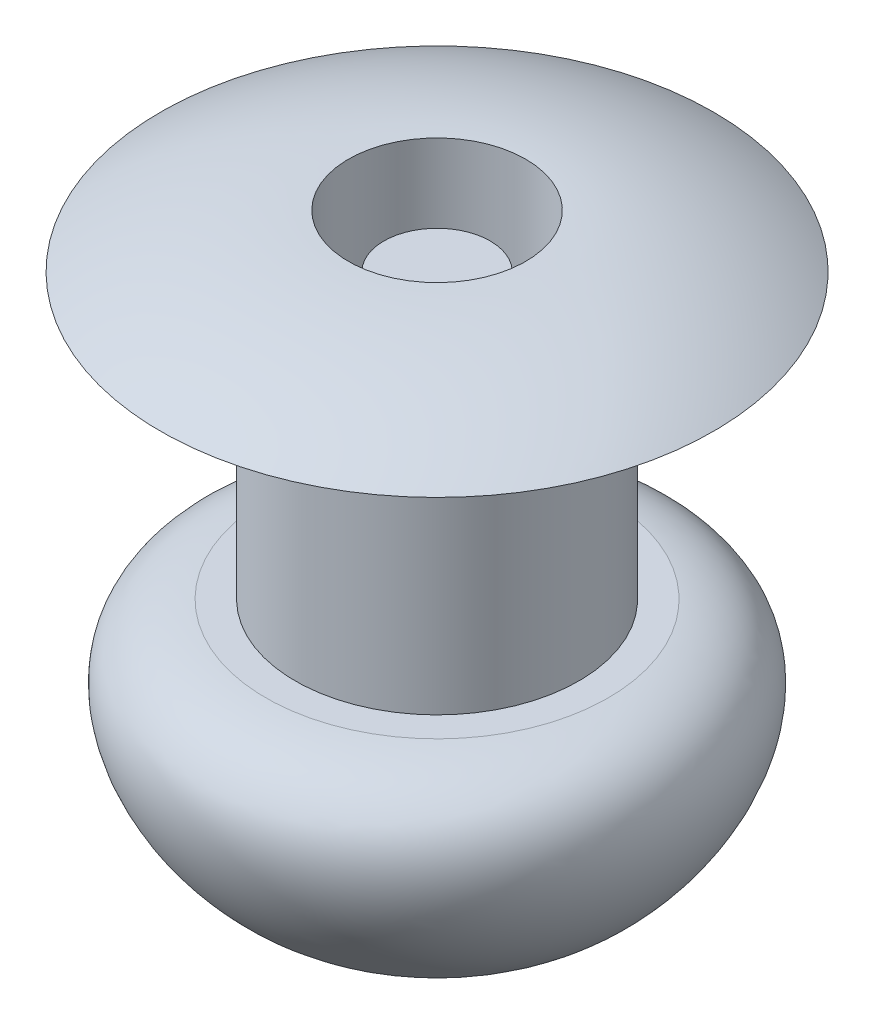
SolidWorks part; units mm, degrees
material "AISI 316 Stal nierdzewna odprężona (SS)"
ref_plane "Płaszczyzna przednia" through (0, 0, 0) normal (0, 0, 1) x (1, 0, 0)
ref_plane "Płaszczyzna górna" through (0, 0, 0) normal (0, 1, 0) x (1, 0, 0)
ref_plane "Płaszczyzna prawa" through (0, 0, 0) normal (1, 0, 0) x (0, 0, -1)
sketch "Szkic1" plane through (0, 0, 0) normal (1, 0, 0) x (0, 0, -1)
  line L0 (0, 0) -> (0, -4.1217)
  line L1 (0, 0) -> (-0.75, 0)
  line L2 (-0.75, 0) -> (-0.75, -4.2007)
  line L3 (-0.75, -4.2007) -> (-1.25, -4.2007)
  line L4 (-1.25, -4.2007) -> (-1.25, 0.75)
  line L5 (-3.9, 0) -> (-2, 0)
  line L6 (-2, 0) -> (-2, -4)
  line L7 (-2, -4) -> (-2.4139, -4)
  line L8 (0, 0) -> (0, 0.75) construction
  line L9 (0, -4.2007) -> (0, -4.1217)
  line L10 (0, -4.2007) -> (0, -5.7007)
  arc A0 (-1.25, 0.75) -> (-3.9, 0) centre (-1.25, -4.3067) ccw
  ellipse E0 centre (0, -4.9507) end of major axis (-1.75, -4.9507) minor radius 0.75 (-0.956, -5.5789) -> (0, -5.7007) ccw
  spline S0 degree 3 poles (-2.4139, -4) (-3.8675, -4.1697) (-3.5289, -6.302) (-1.084, -7.8735) (-0.2718, -5.8749) (-0.956, -5.5789) knots 0 0 0 0 0.464993 0.721928 1 1 1 1
  point P14 (0, 0.75)
  dimension "D1" = 7.8
  dimension "D2" = 2.5
  dimension "D3" = 4
  dimension "D4" = 0.75
  dimension "D5" = 1.5
  dimension "D6" = 1.5
  dimension "D7" = 3.5
  dimension "D8" = 3.1855
  dimension "D9" = 2.5026
  dimension "D10" = 1.9
  dimension "D11" = 1.5789
  dimension "D12" = 0.5792
  dimension "D13" = 4.8278
  dimension "D14" = 3.3858
  dimension "D15" = 2.8395
  dimension "D16" = 1.25
  dimension "D17" = 0.6409
  dimension "D18" = 0.956
  dimension "D19" = 4
revolve "Obrót1" add sketch "Szkic1" angle 360 about L8
